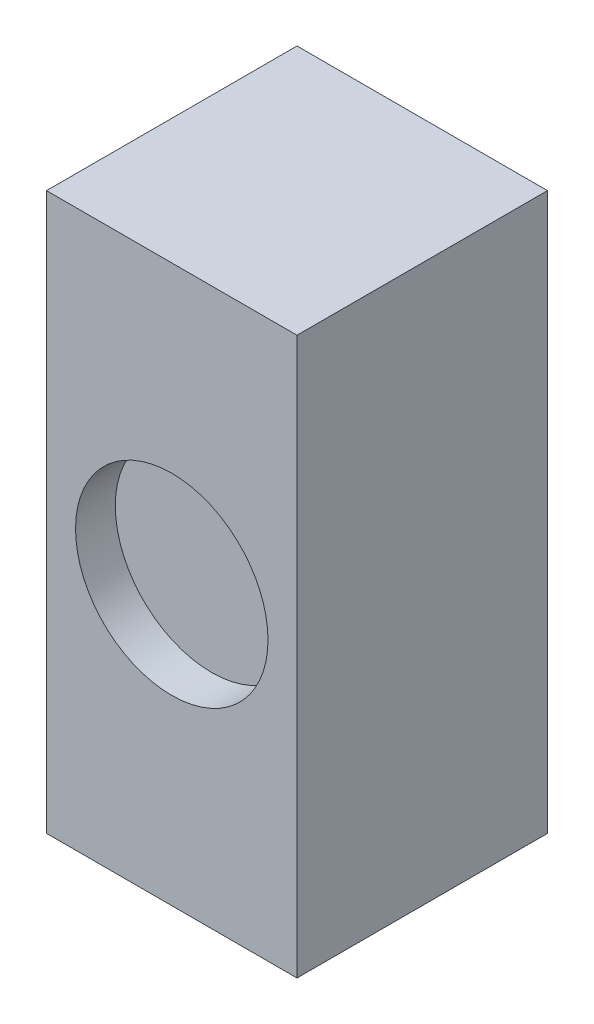
SolidWorks part; units mm, degrees
ref_plane "Front Plane" through (0, 0, 0) normal (0, 0, 1) x (1, 0, 0)
ref_plane "Top Plane" through (0, 0, 0) normal (0, 1, 0) x (1, 0, 0)
ref_plane "Right Plane" through (0, 0, 0) normal (1, 0, 0) x (0, 0, -1)
sketch "Sketch1" plane through (0, 0, 0) normal (0, 1, 0) x (1, 0, 0)
  line L1 (0, -58.2549) -> (0, 58.2549) construction
  line L5 (-58.2549, 0) -> (58.2549, 0) construction
  line L6 (0, 80) -> (-80, 80)
  line L7 (-80, 80) -> (-80, 0)
  line L8 (-80, 0) -> (-80, -80)
  line L9 (-80, -80) -> (0, -80)
  line L10 (80, 0) -> (80, -80)
  line L11 (80, -80) -> (0, -80)
  line L12 (80, 0) -> (80, 80)
  line L13 (80, 80) -> (0, 80)
  circle A0 centre (0, 0) radius 72.136
  point P16 (-80, 0)
  point P17 (0, 80)
  point P18 (80, 0)
  point P19 (0, -80)
extrude "Boss-Extrude1" add sketch "Sketch1" along normal blind 355.6 contours L8 L9 L11 L10 L12 L13 L6 L7
sketch "Sketch3" plane through (0, 0, 80) normal (0, 0, 1) x (1, 0, 0)
  line L0 (80, 355.6) -> (80, 0) construction
  line L1 (-80, 355.6) -> (-80, 0) construction
  line L2 (-80, 355.6) -> (80, 355.6) construction
  circle A0 centre (0, 177.8) radius 61.468
  point P0 (80, 177.8)
  point P1 (0, 177.8)
  point P4 (-80, 177.8)
  point P5 (-218.4995, 215.1229)
  dimension "D1" = 177.8
extrude "Cut-Extrude1" cut sketch "Sketch3" against normal blind 25.4
